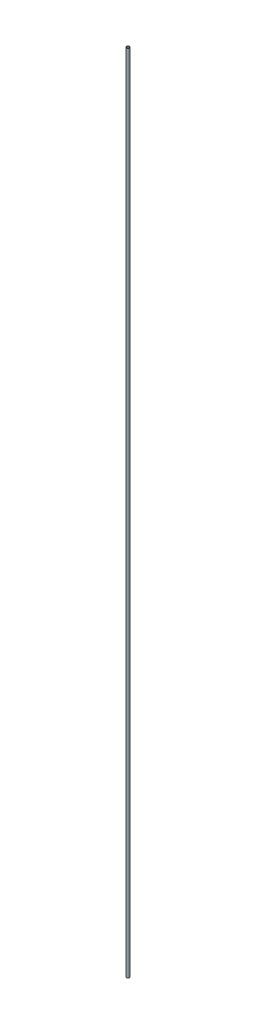
SolidWorks part; units mm, degrees
ref_plane "Front Plane" through (0, 0, 0) normal (0, 0, 1) x (1, 0, 0)
ref_plane "Top Plane" through (0, 0, 0) normal (0, 1, 0) x (1, 0, 0)
ref_plane "Right Plane" through (0, 0, 0) normal (1, 0, 0) x (0, 0, -1)
sketch "Sketch1" plane through (0, 0, 0) normal (0, 1, 0) x (1, 0, 0)
  circle A0 centre (0, 0) radius 1.25
  circle A1 centre (0, 0) radius 1.5
  dimension "D1" = 3
  dimension "D2" = 2.5
extrude "Boss-Extrude1" add sketch "Sketch1" along normal blind 800
